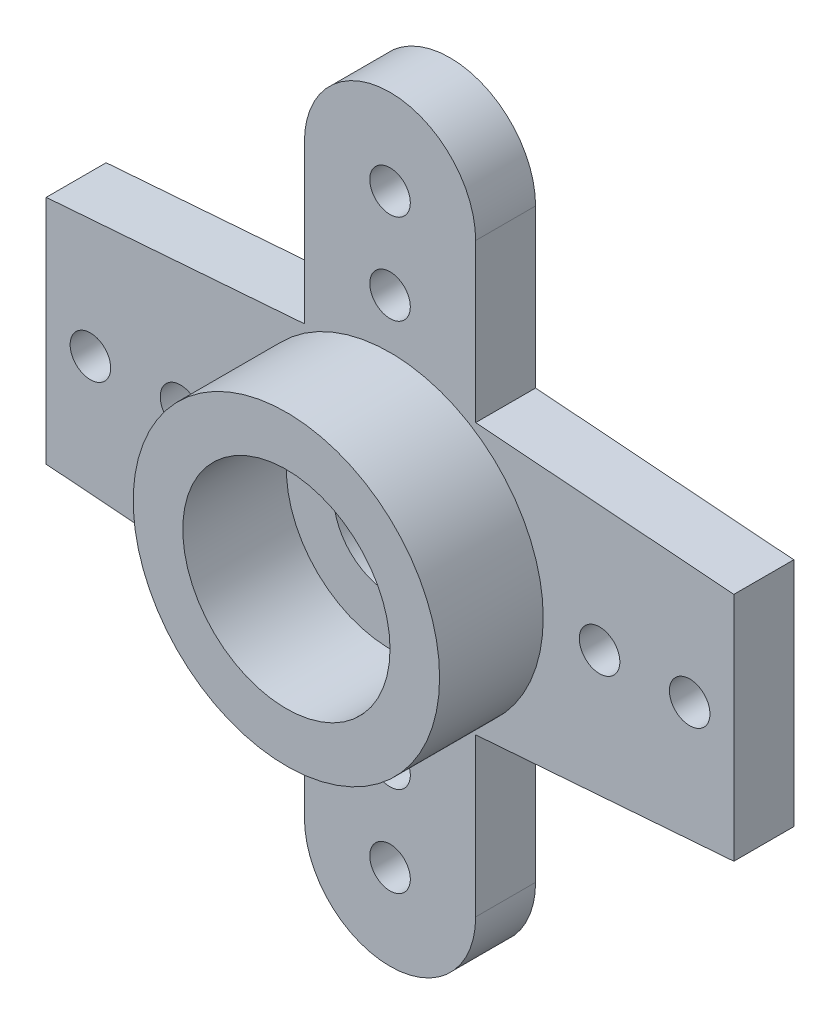
SolidWorks part; units mm, degrees
ref_plane "Ebene vorne" through (0, 0, 0) normal (0, 0, 1) x (1, 0, 0)
ref_plane "Ebene oben" through (0, 0, 0) normal (0, 1, 0) x (1, 0, 0)
ref_plane "Ebene rechts" through (0, 0, 0) normal (1, 0, 0) x (0, 0, -1)
sketch "Skizze1" plane through (0, 0, 0) normal (0, 0, 1) x (1, 0, 0)
  line L0 (0, 3) -> (0, 0) construction
  line L1 (16.65, 0) -> (-16.65, 0) construction
  line L2 (-16.7919, 1.8696) -> (-1.9, 3)
  line L4 (-16.7919, -1.8696) -> (-1.9, -3)
  line L5 (16.7919, -1.8696) -> (1.9, -3)
  line L6 (16.7919, 1.8696) -> (1.9, 3)
  line L7 (-1.9, 3) -> (-1.9, 6.5)
  line L8 (1.9, 3) -> (1.9, 6.5)
  line L9 (1.9, -3) -> (1.9, -6.5)
  line L10 (-1.9, -3) -> (-1.9, -6.5)
  arc A0 (-16.7919, 1.8696) -> (-16.7919, -1.8696) centre (-16.65, 0) ccw
  arc A1 (16.7919, 1.8696) -> (16.7919, -1.8696) centre (16.65, 0) cw
  arc A2 (1.9, 6.5) -> (-1.9, 6.5) centre (0, 6.5) ccw
  arc A3 (1.9, -6.5) -> (-1.9, -6.5) centre (0, -6.5) cw
  dimension "D1" = 3.75
  dimension "D5" = 13
  dimension "D6" = 1.9
  dimension "D2" = 33.3
  dimension "D3" = 6
  dimension "D4" = 3.8
extrude "Aufsatz-Linear austragen1" add sketch "Skizze1" along normal blind 1.33
sketch "Skizze2" plane through (0, 0, 1.33) normal (0, 0, 1) x (1, 0, 0)
  circle A0 centre (0, 0) radius 3.4
  circle A1 centre (0, 0) radius 2.3
  dimension "D1" = 6.8
  dimension "D2" = 4.6
extrude "Aufsatz-Linear austragen2" add sketch "Skizze2" along normal blind 2.3 and the other way up to surface (1.33 mm away) other way up to face at (0, 0, 0)
sketch "Skizze3" plane through (0, 0, 1.33) normal (0, 0, 1) x (1, 0, 0)
  circle A0 centre (0, 0) radius 1.25
  dimension "D1" = 2.5
extrude "Schnitt-Linear austragen1" cut sketch "Skizze3" against normal through all
sketch "Skizze4" plane through (0, 0, 0) normal (0, 0, -1) x (-1, 0, 0)
  circle A0 centre (0, 0) radius 2.35
  dimension "D1" = 4.7
extrude "Schnitt-Linear austragen2" cut sketch "Skizze4" against normal blind 1.1
sketch "Skizze5" plane through (0, 0, 1.33) normal (0, 0, 1) x (1, 0, 0)
  line L0 (0, 6.5) -> (0, 0) construction
  line L1 (0, 0) -> (-16.65, 0) construction
  line L2 (0, 4.5) -> (0, -2) construction
  circle A0 centre (0, 6.5) radius 0.45
  circle A1 centre (-16.65, 0) radius 0.45
  circle A2 centre (0, 4.5) radius 0.45
  circle A3 centre (-14.65, 0) radius 0.45
  circle A4 centre (-12.65, 0) radius 0.45
  circle A5 centre (-10.65, 0) radius 0.45
  circle A6 centre (-8.65, 0) radius 0.45
  circle A7 centre (-6.65, 0) radius 0.45
  circle A8 centre (-4.65, 0) radius 0.45
  circle A9 centre (0, -4.5) radius 0.45
  circle A10 centre (0, -6.5) radius 0.45
  circle A11 centre (4.65, 0) radius 0.45
  circle A12 centre (6.65, 0) radius 0.45
  circle A13 centre (8.65, 0) radius 0.45
  circle A14 centre (10.65, 0) radius 0.45
  circle A15 centre (12.65, 0) radius 0.45
  circle A16 centre (14.65, 0) radius 0.45
  circle A17 centre (16.65, 0) radius 0.45
  dimension "D1" = 0.9
  dimension "D2" = 2
  dimension "D3" = 7
extrude "Schnitt-Linear austragen3" cut sketch "Skizze5" against normal through all
sketch "Skizze6" plane through (0, 0, 0) normal (0, 0, -1) x (-1, 0, 0)
  line L0 (-7.6307, -0.0695) -> (-7.6307, 5.6419)
  line L5 (-7.6307, 5.6419) -> (-18.9818, 5.6419)
  line L6 (-18.9818, 5.6419) -> (-18.9818, -4.0187)
  line L7 (-18.9818, -4.0187) -> (-7.6307, -4.0187)
  line L8 (-7.6307, -4.0187) -> (-7.6307, -0.0695)
  line L9 (0, 10.4796) -> (0, -9.9035) construction
  line L10 (7.6307, -4.0187) -> (7.6307, -0.0695)
  line L11 (18.9818, -4.0187) -> (7.6307, -4.0187)
  line L12 (18.9818, 5.6419) -> (18.9818, -4.0187)
  line L13 (7.6307, 5.6419) -> (18.9818, 5.6419)
  line L14 (7.6307, -0.0695) -> (7.6307, 5.6419)
extrude "Schnitt-Linear austragen4" cut sketch "Skizze6" against normal up to surface (1.33 mm away) up to face at (0.45, 6.5, 1.33)
